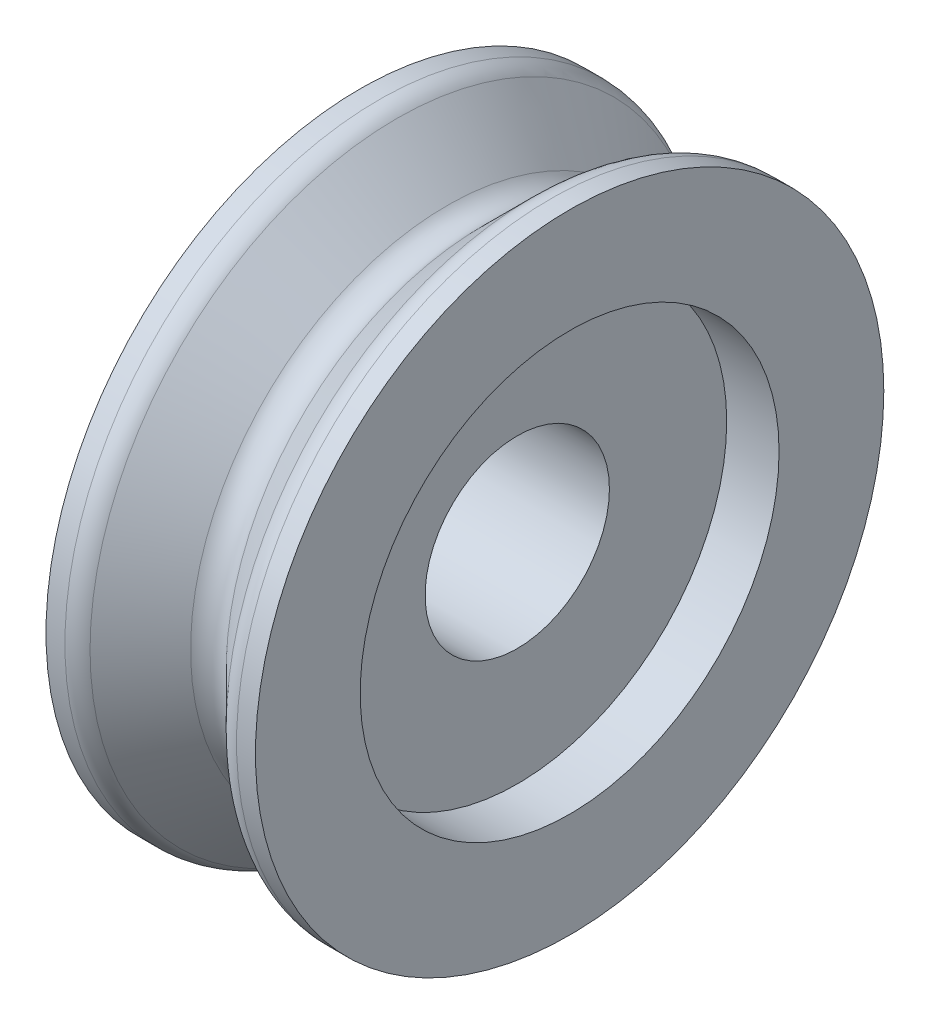
SolidWorks part; units mm, degrees
material "ABS"
ref_plane "Front Plane" through (0, 0, 0) normal (0, 0, 1) x (1, 0, 0)
ref_plane "Top Plane" through (0, 0, 0) normal (0, 1, 0) x (1, 0, 0)
ref_plane "Right Plane" through (0, 0, 0) normal (1, 0, 0) x (0, 0, -1)
sketch "Sketch1" plane through (0, 0, 0) normal (0, 0, 1) x (1, 0, 0)
  line L0 (-3.175, 6.35) -> (-4.7625, 6.35)
  line L1 (-4.7625, 6.35) -> (-4.7625, 2.794)
  line L2 (-4.7625, 2.794) -> (-9.525, 2.794)
  line L3 (-9.525, 2.794) -> (-9.525, 9.525)
  line L4 (-9.525, 9.525) -> (-8.9516, 9.525)
  line L5 (-8.4128, 9.3018) -> (-6.8888, 7.7778)
  line L6 (-5.8112, 7.7778) -> (-4.2872, 9.3018)
  line L7 (-3.7484, 9.525) -> (-3.175, 9.525)
  line L8 (-3.175, 9.525) -> (-3.175, 6.35)
  line L10 (0, 0) -> (-16.6525, 0) construction
  arc A0 (-8.9516, 9.525) -> (-8.4128, 9.3018) centre (-8.9516, 8.763) cw
  arc A1 (-4.2872, 9.3018) -> (-3.7484, 9.525) centre (-3.7484, 8.763) cw
  arc A2 (-6.8888, 7.7778) -> (-5.8112, 7.7778) centre (-6.35, 8.3166) ccw
  point P10 (-8.636, 9.525)
  point P17 (-4.064, 9.525)
  dimension "D8" = 0.762
  dimension "D1" = 4.7625
  dimension "D2" = 2.794
  dimension "D3" = 4.7625
  dimension "D4" = 6.731
  dimension "D5" = 6.35
  dimension "D6" = 6.35
  dimension "D7" = 4.572
revolve "Revolve1" add sketch "Sketch1" angle 360 about L10
